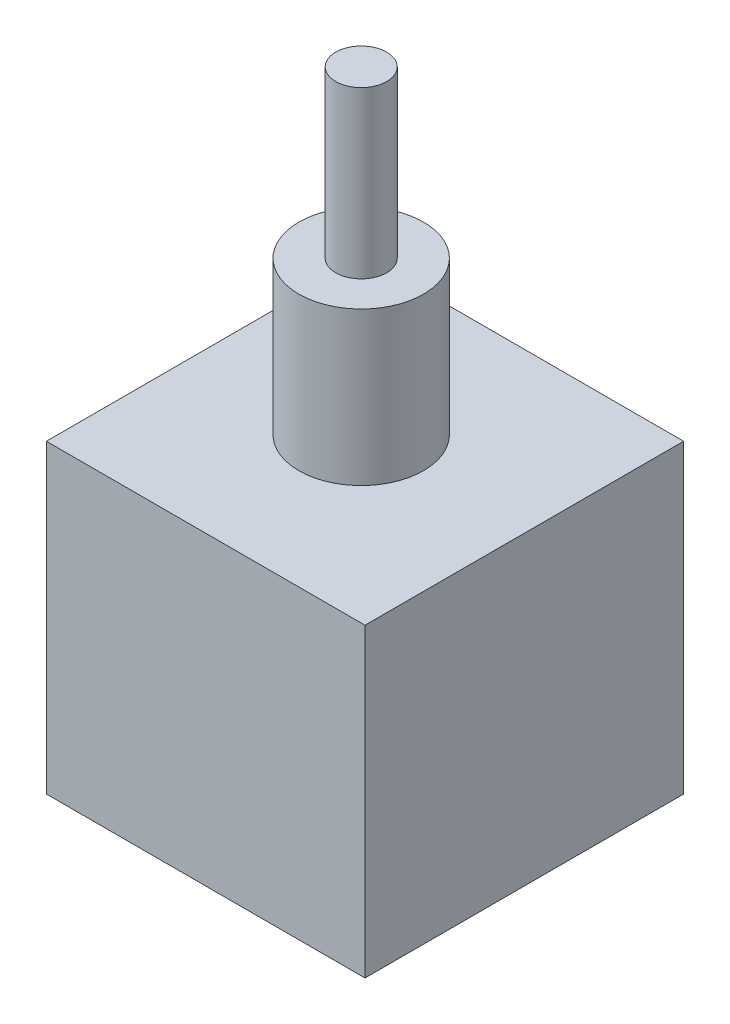
SolidWorks part; units mm, degrees
ref_plane "Спереди" through (0, 0, 0) normal (0, 0, 1) x (1, 0, 0)
ref_plane "Сверху" through (0, 0, 0) normal (0, 1, 0) x (1, 0, 0)
ref_plane "Справа" through (0, 0, 0) normal (1, 0, 0) x (0, 0, -1)
other "Configuration Table"
sketch "Эскиз1" plane through (0, 0, 0) normal (0, 1, 0) x (1, 0, 0)
  line L1 (-14.2865, 14.6433) -> (15.7135, 14.6433)
  line L2 (-14.2865, 14.6433) -> (-14.2865, -15.3567)
  line L3 (-14.2865, -15.3567) -> (15.7135, -15.3567)
  line L4 (15.7135, 14.6433) -> (15.7135, -15.3567)
  dimension "D1" = 30
  dimension "D2" = 30
extrude "высота " add sketch "Эскиз1" along normal blind 28.77
sketch "Эскиз2" plane through (0, 28.77, 0) normal (0, 1, 0) x (1, 0, 0)
  circle A0 centre (0, 0) radius 5.875
  dimension "D1" = 11.75
sketch "Эскиз3" plane through (0, 0, 0) normal (0, 0, 1) x (1, 0, 0)
  line L0 (0, 49.97) -> (0, -1.7648) construction
extrude "Бобышка-Вытянуть2" add sketch "Эскиз2" along normal blind 14.4 contours A0
sketch "Эскиз4" plane through (0, 43.17, 0) normal (0, 1, 0) x (1, 0, 0)
  circle A0 centre (0, 0) radius 2.4
  dimension "D1" = 4.8
extrude "Бобышка-Вытянуть3" add sketch "Эскиз4" along normal blind 15.6
sketch "Эскиз5" plane through (0, 0, 0) normal (0, -1, 0) x (1, 0, 0)
  line L0 (0, 0) -> (39.9543, 0) construction
  line L1 (0, 0) -> (0, 32.8196) construction
  circle A0 centre (8, 0) radius 2.5
  circle A1 centre (-8, 0) radius 2.5
  dimension "D1" = 5
  dimension "D2" = 8
extrude "Вырез-Вытянуть2" cut sketch "Эскиз5" against normal blind 15 contours A0 | A1
